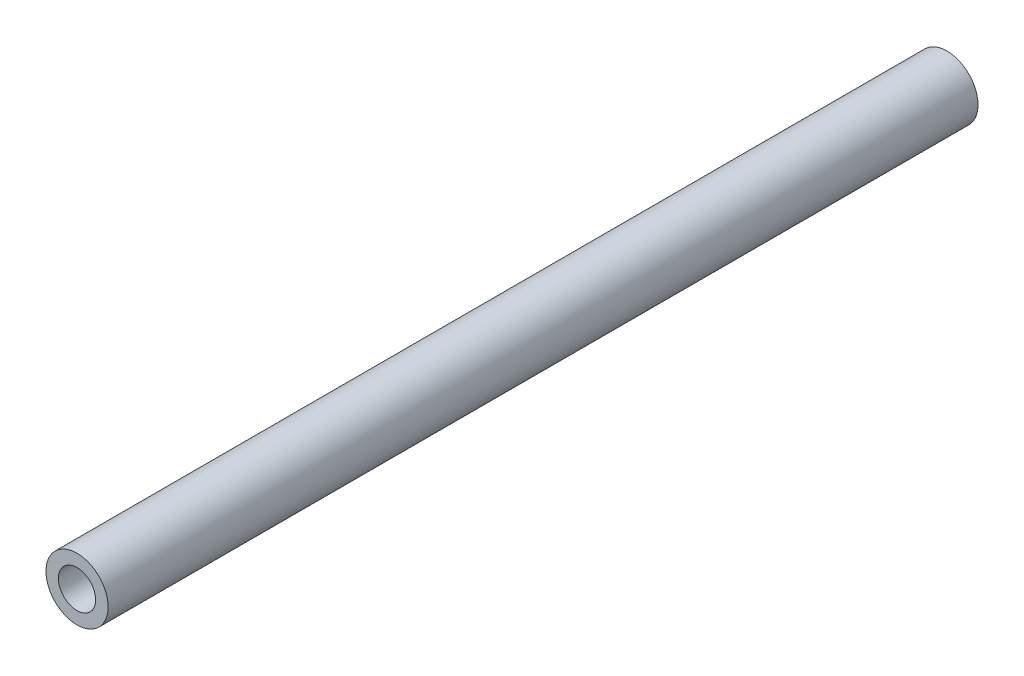
SolidWorks part; units mm, degrees
ref_plane "前视基准面" through (0, 0, 0) normal (0, 0, 1) x (1, 0, 0)
ref_plane "上视基准面" through (0, 0, 0) normal (0, 1, 0) x (1, 0, 0)
ref_plane "右视基准面" through (0, 0, 0) normal (1, 0, 0) x (0, 0, -1)
other "Configuration Table"
sketch "草图1" plane through (0, 0, 0) normal (0, 0, 1) x (1, 0, 0)
  circle A0 centre (0, 0) radius 2.5
  circle A1 centre (0, 0) radius 1.5
  dimension "D1" = 3
  dimension "D2" = 5
extrude "凸台-拉伸1" add sketch "草图1" along normal blind 70
